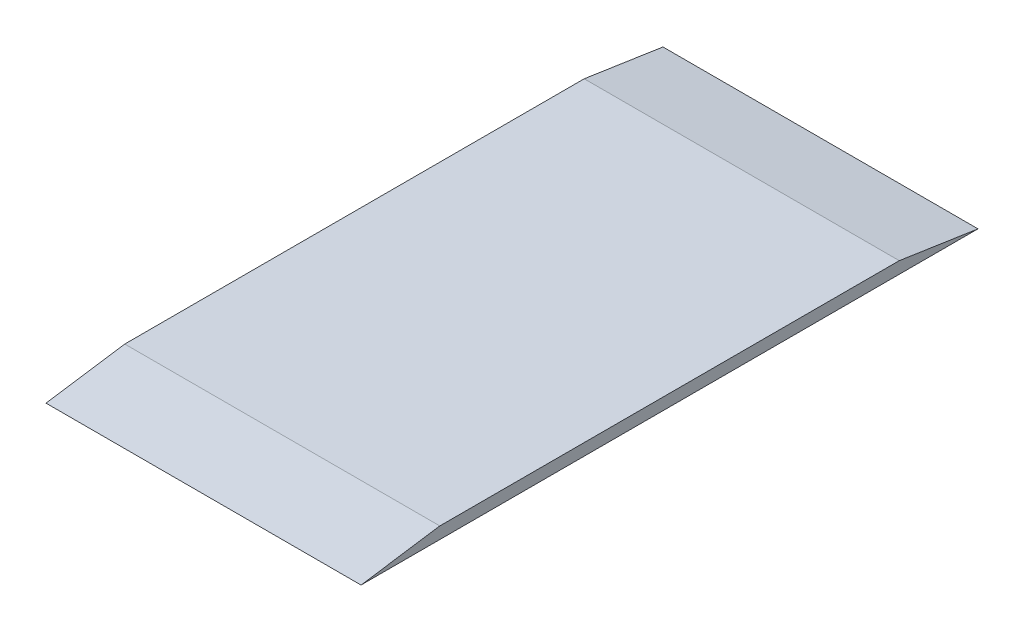
SolidWorks part; units mm, degrees
ref_plane "Front Plane" through (0, 0, 0) normal (0, 0, 1) x (1, 0, 0)
ref_plane "Top Plane" through (0, 0, 0) normal (0, 1, 0) x (1, 0, 0)
ref_plane "Right Plane" through (0, 0, 0) normal (1, 0, 0) x (0, 0, -1)
sketch "Sketch1" plane through (0, 0, 0) normal (1, 0, 0) x (0, 0, -1)
  line L0 (23.5, 0) -> (-23.5, 0)
  line L1 (-23.5, 0) -> (-17.5, 0.9)
  line L2 (-17.5, 0.9) -> (17.5, 0.9)
  line L3 (17.5, 0.9) -> (23.5, 0)
extrude "Boss-Extrude1" add sketch "Sketch1" along normal mid plane 24
